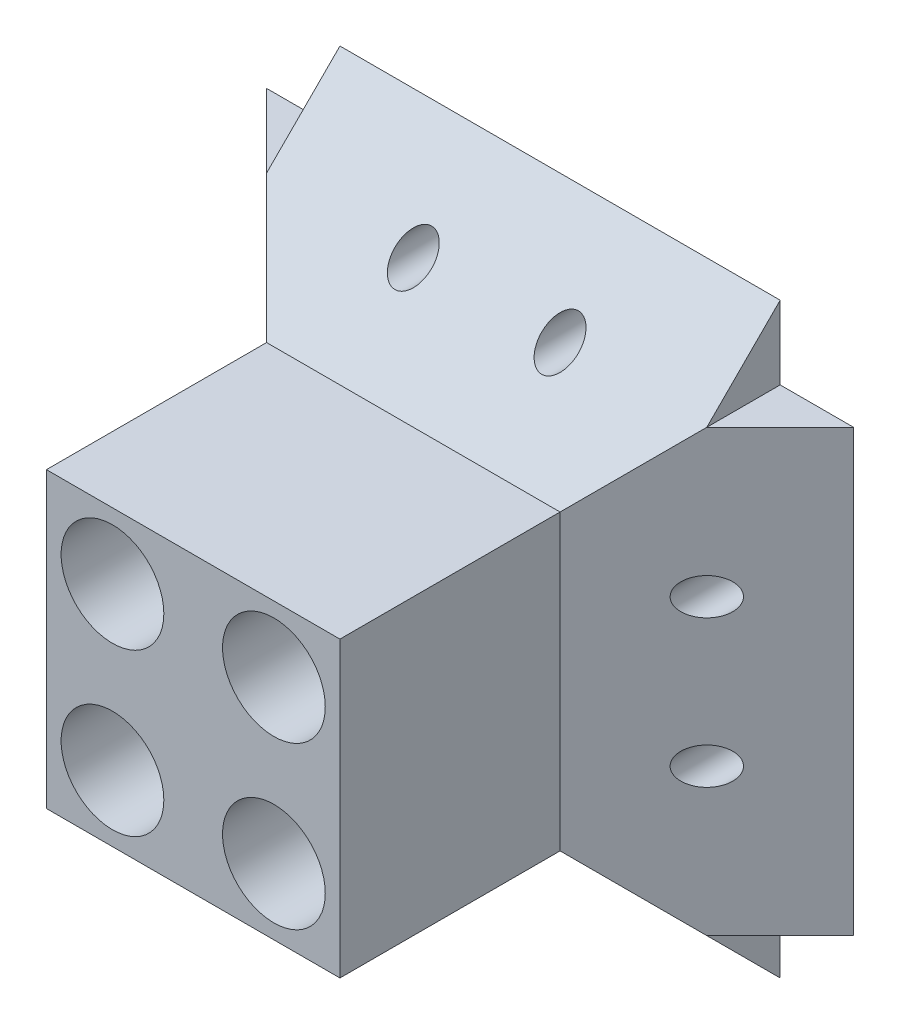
SolidWorks part; units mm, degrees
ref_plane "정면" through (0, 0, 0) normal (0, 0, 1) x (1, 0, 0)
ref_plane "윗면" through (0, 0, 0) normal (0, 1, 0) x (1, 0, 0)
ref_plane "우측면" through (0, 0, 0) normal (1, 0, 0) x (0, 0, -1)
sketch "스케치1" plane through (0, 0, 0) normal (0, 0, 1) x (1, 0, 0)
  line L1 (-10, 10) -> (10, 10)
  line L2 (-10, 10) -> (-10, -10)
  line L3 (-10, -10) -> (10, -10)
  line L4 (10, 10) -> (10, -10)
  line L5 (-10, 10) -> (10, -10) construction
  line L6 (-10, -10) -> (10, 10) construction
  point P0 (0, 0)
  dimension "D1" = 20
  dimension "D2" = 20
extrude "보스-돌출1" add sketch "스케치1" along normal blind 40
sketch "스케치2" plane through (10, 0, 0) normal (1, 0, 0) x (0, 0, -1)
  line L0 (0, -10) -> (0, 10) construction
  line L1 (-15, 7.5) -> (-5, 7.5)
  line L2 (-15, 7.5) -> (-15, -7.5)
  line L3 (-15, -7.5) -> (-5, -7.5)
  line L4 (-5, 7.5) -> (-5, -7.5)
  line L5 (-15, 7.5) -> (-5, -7.5) construction
  line L6 (-15, -7.5) -> (-5, 7.5) construction
  line L7 (-40, -10) -> (0, -10) construction
  point P0 (-10, 0)
  dimension "D1" = 10
  dimension "D2" = 10
  dimension "D3" = 15
  dimension "D4" = 10
extrude "컷-돌출1" cut sketch "스케치2" against normal blind 7.0711
sketch "스케치4" plane through (0, 0, 0) normal (0, 1, 0) x (1, 0, 0)
  line L0 (0, -30.773) -> (0, 0.8163) construction
pattern_circular "원형 패턴1" count 4 over 360 about axis through (0, 0, 0) along (0, 0, 1) of "컷-돌출1"
sketch "스케치5" plane through (0, 0, 40) normal (0, 0, 1) x (1, 0, 0)
  line L0 (-10, 10) -> (-10, -10) construction
  line L1 (-10, -10) -> (10, -10) construction
  line L2 (10, -10) -> (10, 10) construction
  line L3 (10, 10) -> (-10, 10) construction
  circle A0 centre (-5.5, 5.5) radius 3.5
  circle A1 centre (5.5, 5.5) radius 3.5
  circle A2 centre (-5.5, -5.5) radius 3.5
  circle A3 centre (5.5, -5.5) radius 3.5
  dimension "D1" = 7
  dimension "D2" = 7
  dimension "D3" = 7
  dimension "D4" = 7
  dimension "D5" = 4.5
  dimension "D6" = 4.5
  dimension "D7" = 4.5
  dimension "D8" = 4.5
  dimension "D9" = 4.5
  dimension "D10" = 4.5
  dimension "D11" = 4.5
  dimension "D12" = 4.5
extrude "컷-돌출2" cut sketch "스케치5" along a picked direction on the side against the normal blind 25
sketch "스케치6" plane through (0, 0, 0) normal (0, 0, -1) x (-1, 0, 0)
  line L5 (-14.8088, -2.95) -> (-14.8088, 2.95)
  line L7 (-14.8088, 2.95) -> (-2.95, 2.95)
  line L8 (-2.95, 2.95) -> (-2.95, 12.3603)
  line L10 (-2.95, 12.3603) -> (2.95, 12.3603)
  line L11 (2.95, 12.3603) -> (2.95, 2.95)
  line L12 (2.95, 2.95) -> (13.8521, 2.95)
  line L14 (13.8521, 2.95) -> (13.8521, -2.95)
  line L15 (13.8521, -2.95) -> (2.95, -2.95)
  line L16 (2.95, -2.95) -> (2.95, -13.9757)
  line L18 (2.95, -13.9757) -> (-2.95, -13.9757)
  line L19 (-2.95, -13.9757) -> (-2.95, -2.95)
  line L20 (-2.95, -2.95) -> (-14.8088, -2.95)
  dimension "D1" = 5.9
  dimension "D2" = 2.95
  dimension "D3" = 5.9
  dimension "D4" = 5.9
  dimension "D5" = 5.9
  dimension "D6" = 2.95
  dimension "D7" = 2.95
  dimension "D8" = 2.95
extrude "컷-돌출3" cut sketch "스케치6" against normal blind 5
sketch "스케치8" plane through (0, 0, 0) normal (0, 1, 0) x (1, 0, 0)
  line L5 (-11.0684, 1.3381) -> (11.5394, 1.3381)
  line L6 (-11.0684, 1.3381) -> (-11.0684, -40.7573)
  line L7 (-11.0684, -40.7573) -> (11.5394, -40.7573)
  line L8 (11.5394, 1.3381) -> (11.5394, -40.7573)
sketch "스케치9" plane through (0, 0, 5) normal (0, 0, -1) x (-1, 0, 0)
  line L1 (-2.9289, 2.9289) -> (2.95, 2.9289)
  line L2 (-2.9289, 2.9289) -> (-2.9289, -2.95)
  line L3 (-2.9289, -2.95) -> (2.95, -2.95)
  line L4 (2.95, 2.9289) -> (2.95, -2.95)
extrude "컷-돌출5" cut sketch "스케치9" against normal blind 5
sketch "스케치11" plane through (10, 0, 0) normal (1, 0, 0) x (0, 0, -1)
  line L1 (-15, 15) -> (-25, 15)
  line L2 (-15, 15) -> (-15, -15)
  line L3 (-15, -15) -> (-25, -15)
  line L4 (-25, 15) -> (-25, -15)
  dimension "D1" = 30
  dimension "D2" = 10
  dimension "D3" = 15
extrude "보스-돌출2" add sketch "스케치11" along normal blind 10
sketch "스케치12" plane through (0, 15, 0) normal (0, 1, 0) x (1, 0, 0)
  line L0 (20, -15) -> (10, -25)
  line L1 (10, -25) -> (20, -25)
  line L2 (20, -25) -> (20, -15)
extrude "컷-돌출6" cut sketch "스케치12" against normal blind 30
sketch "스케치14" plane through (0, 0, 0) normal (1, 0, 0) x (0, 0, -1)
  line L0 (-45.6435, 0) -> (9.8052, 0) construction
sketch "스케치13" plane through (0, 0, 15) normal (0, 0, -1) x (-1, 0, 0)
  line L0 (-10, 2.95) -> (-10, 10) construction
  line L1 (-10, -10) -> (-10, -2.95) construction
  line L4 (-20, -15) -> (-10, -15) construction
  line L5 (-20, 15) -> (-10, 15) construction
  circle A0 centre (-15, -5) radius 1.25
  circle A1 centre (-15, 5) radius 1.25
  dimension "D5" = 2.5
  dimension "D6" = 2.5
  dimension "D1" = 5
  dimension "D2" = 5
  dimension "D3" = 10
  dimension "D4" = 10
extrude "컷-돌출7" cut sketch "스케치13" against normal blind 10
pattern_circular "원형 패턴2" count 4 over 360 about axis through (0, 0, 0) along (0, 0, 1) of "컷-돌출7", "컷-돌출6", "보스-돌출2"
ref_plane "평면1" through (0, 0, 25) normal (0, 0, -1) x (-1, 0, 0)
sketch "스케치16" plane through (0, -10, 0) normal (0, -1, 0) x (1, 0, 0)
  line L0 (-2.9289, 10) -> (2.9289, 10) construction
  line L1 (10, 0) -> (-10, 0)
  line L2 (10, 0) -> (10, 10)
  line L3 (10, 10) -> (-10, 10)
  line L4 (-10, 0) -> (-10, 10)
  dimension "D1" = 0
extrude "컷-돌출11" cut sketch "스케치16" against normal blind 40
sketch "스케치17" plane through (0, 0, 10) normal (0, 0, -1) x (-1, 0, 0)
  line L1 (-10, 10) -> (10, 10)
  line L2 (-10, 10) -> (-10, -10)
  line L3 (-10, -10) -> (10, -10)
  line L4 (10, 10) -> (10, -10)
  line L5 (-10, 10) -> (10, -10) construction
  line L6 (-10, -10) -> (10, 10) construction
  line L7 (-2.9289, 2.9289) -> (2.9289, 2.9289)
  line L8 (-2.9289, 2.9289) -> (-2.9289, -2.9289)
  line L9 (-2.9289, -2.9289) -> (2.9289, -2.9289)
  line L10 (2.9289, 2.9289) -> (2.9289, -2.9289)
  line L11 (-2.9289, 2.9289) -> (2.9289, -2.9289) construction
  line L12 (-2.9289, -2.9289) -> (2.9289, 2.9289) construction
  point P0 (0, 0)
  point P7 (0, 0)
extrude "컷-돌출12" cut sketch "스케치17" against normal blind 5
sketch "스케치18" plane through (0, 10, 0) normal (0, -1, 0) x (1, 0, 0)
  line L0 (10, 25) -> (15, 25)
  line L1 (15, 25) -> (15, 20)
  line L2 (15, 20) -> (10, 25)
extrude "컷-돌출13" cut sketch "스케치18" against normal blind 10 and the other way through all
